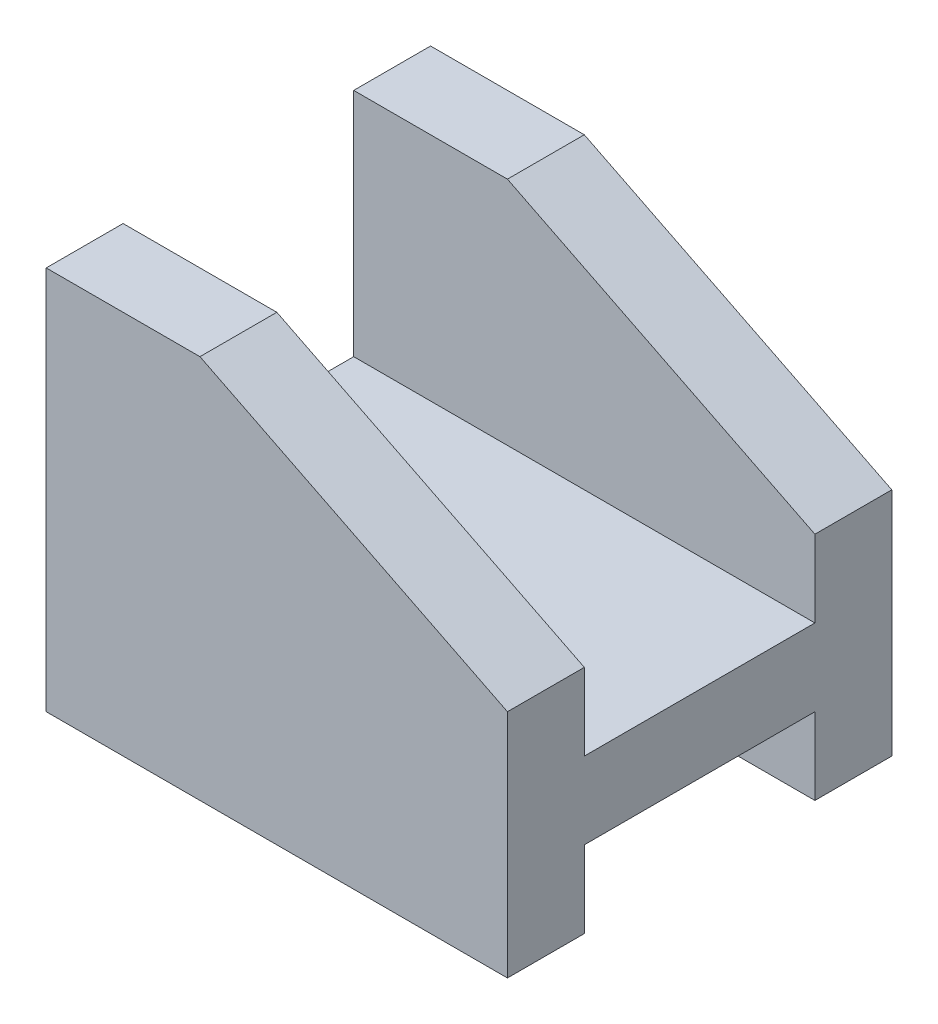
SolidWorks part; units mm, degrees
ref_plane "Front Plane" through (0, 0, 0) normal (0, 0, 1) x (1, 0, 0)
ref_plane "Top Plane" through (0, 0, 0) normal (0, 1, 0) x (1, 0, 0)
ref_plane "Right Plane" through (0, 0, 0) normal (1, 0, 0) x (0, 0, -1)
sketch "Sketch2" plane through (0, 0, 0) normal (1, 0, 0) x (0, 0, -1)
  line L1 (-15.875, -15.875) -> (15.875, -15.875)
  line L2 (-15.875, -15.875) -> (-15.875, 15.875)
  line L3 (-15.875, 15.875) -> (15.875, 15.875)
  line L4 (15.875, -15.875) -> (15.875, 15.875)
  line L5 (-15.875, -15.875) -> (15.875, 15.875) construction
  line L6 (-15.875, 15.875) -> (15.875, -15.875) construction
  point P0 (0, 0)
  dimension "D1" = 31.75
  dimension "D2" = 31.75
extrude "Boss-Extrude2" add sketch "Sketch2" along normal mid plane 38.1
sketch "Sketch4" plane through (0, 0, 0) normal (1, 0, 0) x (0, 0, -1)
  line L0 (15.875, 15.875) -> (-15.875, 15.875) construction
  line L1 (-9.525, -3.175) -> (9.525, -3.175)
  line L2 (-9.525, -3.175) -> (-9.525, 15.875)
  line L3 (-9.525, 15.875) -> (9.525, 15.875)
  line L4 (15.875, -15.875) -> (15.875, 15.875)
  line L5 (15.875, 15.875) -> (-15.875, 15.875)
  line L6 (-15.875, 15.875) -> (-15.875, -15.875)
  line L7 (-15.875, -15.875) -> (15.875, -15.875)
  line L8 (15.875, -15.875) -> (15.875, 15.875)
  line L9 (15.875, 15.875) -> (-15.875, 15.875)
  line L10 (-15.875, 15.875) -> (-15.875, -15.875)
  line L11 (-15.875, -15.875) -> (15.875, -15.875)
  line L12 (9.525, -3.175) -> (9.525, 15.875)
  line L13 (-9.525, -3.175) -> (9.525, 15.875) construction
  line L14 (-9.525, 15.875) -> (9.525, -3.175) construction
  point P2 (0, 6.35)
  dimension "D2" = 19.05
  dimension "D3" = 19.05
  dimension "D1" = 0
extrude "Cut-Extrude1" cut sketch "Sketch4" against normal through all and the other way through all contours L2 L3 L12 L1
sketch "Sketch5" plane through (0, 0, 0) normal (1, 0, 0) x (0, 0, -1)
  line L1 (-9.525, -9.525) -> (9.525, -9.525)
  line L2 (-9.525, -9.525) -> (-9.525, -15.875)
  line L3 (-9.525, -15.875) -> (9.525, -15.875)
  line L4 (9.525, -9.525) -> (9.525, -15.875)
  line L5 (-9.525, -9.525) -> (9.525, -15.875) construction
  line L6 (-9.525, -15.875) -> (9.525, -9.525) construction
  line L14 (-9.525, -3.175) -> (-9.525, 15.875)
  line L15 (-9.525, 15.875) -> (-15.875, 15.875)
  line L16 (-15.875, 15.875) -> (-15.875, -15.875)
  line L17 (-15.875, -15.875) -> (15.875, -15.875)
  line L18 (15.875, -15.875) -> (15.875, 15.875)
  line L19 (15.875, 15.875) -> (9.525, 15.875)
  line L20 (9.525, 15.875) -> (9.525, -3.175)
  line L21 (9.525, -3.175) -> (-9.525, -3.175)
  line L22 (-9.525, -3.175) -> (-9.525, 15.875)
  line L23 (-9.525, 15.875) -> (-15.875, 15.875)
  line L24 (-15.875, 15.875) -> (-15.875, -15.875)
  line L25 (-15.875, -15.875) -> (15.875, -15.875)
  line L26 (15.875, -15.875) -> (15.875, 15.875)
  line L27 (15.875, 15.875) -> (9.525, 15.875)
  line L28 (9.525, 15.875) -> (9.525, -3.175)
  line L29 (9.525, -3.175) -> (-9.525, -3.175)
  point P0 (0, -12.7)
  dimension "D2" = 6.35
  dimension "D3" = 19.05
  dimension "D1" = 0
extrude "Cut-Extrude2" cut sketch "Sketch5" against normal through all and the other way through all contours L4 L1 L2 L3
sketch "Sketch6" plane through (0, 0, 0) normal (0, 0, 1) x (1, 0, 0)
  line L0 (19.05, 15.875) -> (19.05, 3.175)
  line L1 (19.05, 15.875) -> (19.05, -15.875) construction
  line L2 (19.05, 3.175) -> (-6.35, 15.875)
  line L3 (19.05, 15.875) -> (-19.05, 15.875) construction
  line L4 (-6.35, 15.875) -> (19.05, 15.875)
  dimension "D1" = 25.4
  dimension "D2" = 12.7
extrude "Cut-Extrude3" cut sketch "Sketch6" against normal through all and the other way through all
